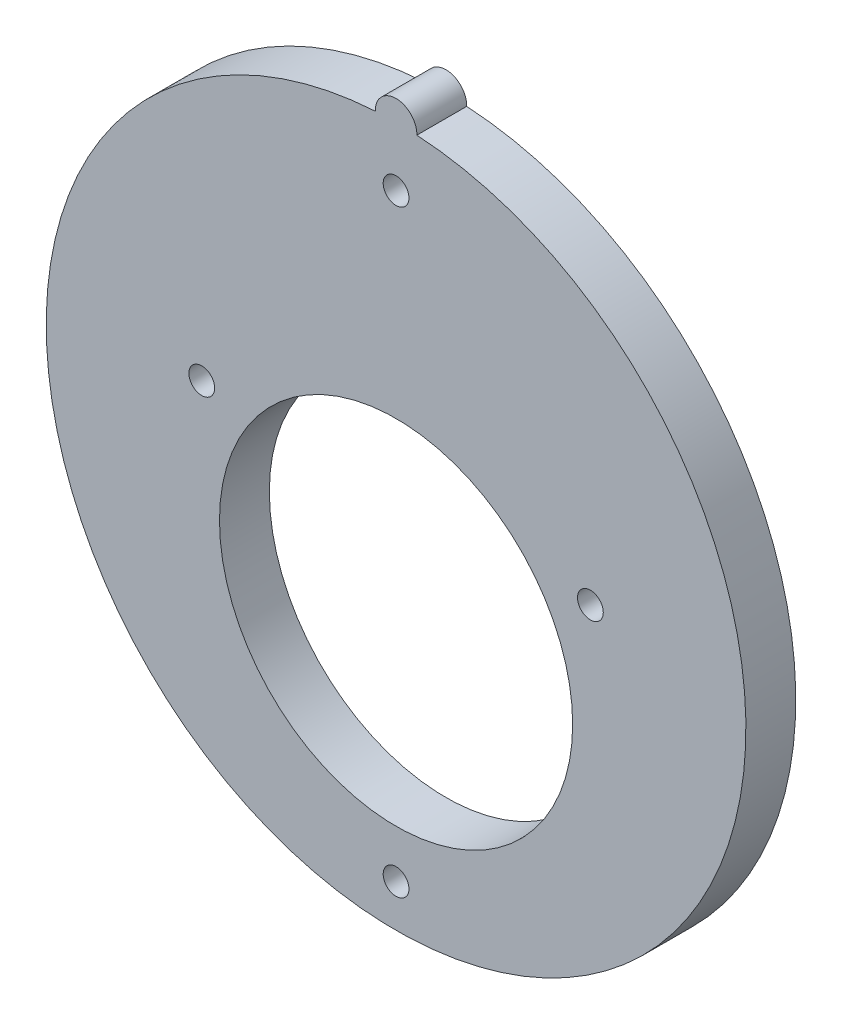
SolidWorks part; units mm, degrees
ref_plane "Płaszczyzna przednia" through (0, 0, 0) normal (0, 0, 1) x (1, 0, 0)
ref_plane "Płaszczyzna górna" through (0, 0, 0) normal (0, 1, 0) x (1, 0, 0)
ref_plane "Płaszczyzna prawa" through (0, 0, 0) normal (1, 0, 0) x (0, 0, -1)
sketch "Szkic1" plane through (0, 0, 0) normal (0, 0, 1) x (1, 0, 0)
  arc A0 (38.7806, 73.9078) -> (43.7784, 73.9078) centre (41.2795, 31.882) ccw
  arc A1 (43.7784, 73.9078) -> (38.7806, 73.9078) centre (41.2795, 73.982) ccw
  dimension "D1" = 84.2
  dimension "D2" = 5
extrude "Dodanie-wyciągnięcie1" add sketch "Szkic1" along normal blind 6
sketch "Szkic3" plane through (0, 0, 6) normal (0, 0, 1) x (1, 0, 0)
  line L0 (41.2795, 76.482) -> (41.2795, 1.7316) construction
  arc A1 (43.7784, 73.9078) -> (38.7806, 73.9078) centre (41.2795, 73.982) ccw construction
  circle A2 centre (41.2795, 21.882) radius 21.25
  arc A3 (38.7806, 73.9078) -> (43.7784, 73.9078) centre (41.2795, 31.882) ccw construction
  dimension "D1" = 42.5
  dimension "D2" = 10
extrude "Wytnij-wyciągnięcie1" cut sketch "Szkic3" against normal blind 10
sketch "Szkic4" plane through (0, 0, 6) normal (0, 0, 1) x (1, 0, 0)
  line L0 (41.2795, -10.218) -> (41.2795, -3.568) construction
  line L1 (41.2795, -3.568) -> (41.2795, 21.882) construction
  line L2 (17.8968, 35.382) -> (41.2795, 21.882) construction
  line L3 (41.2795, 21.882) -> (64.6622, 35.382) construction
  line L4 (41.2795, 21.882) -> (41.2795, 69.1257) construction
  arc A0 (38.7806, 73.9078) -> (43.7784, 73.9078) centre (41.2795, 31.882) ccw construction
  circle A1 centre (41.2795, -5.118) radius 1.55
  circle A2 centre (17.8968, 35.382) radius 1.55
  circle A3 centre (64.6622, 35.382) radius 1.55
  circle A4 centre (41.2795, 21.882) radius 21.25 construction
  circle A5 centre (41.2795, 66.882) radius 1.55
  dimension "D1" = 3.1
  dimension "D2" = 3.1
  dimension "D3" = 3.1
  dimension "D4" = 27
  dimension "D5" = 27
  dimension "D7" = 27
  dimension "D9" = 3.1
  dimension "D10" = 45
  dimension "D6" = 120
  dimension "D8" = 120
extrude "Wytnij-wyciągnięcie2" cut sketch "Szkic4" against normal blind 10
sketch "Szkic5" plane through (0, 0, 6) normal (0, 0, 1) x (1, 0, 0)
  line L0 (41.2795, 76.482) -> (41.2795, -7.4662) construction
  arc A0 (43.7784, 73.9078) -> (38.7806, 73.9078) centre (41.2795, 73.982) ccw construction
  point P6 (41.2795, 21.882)
equation "\"tolerancja_wpusy\"=0.2"
equation "\"dlugosc_wpustu_duzy\"=20"
equation "\"srednica_otworu_M3\"=3.1"
equation "\"szerokosc_nogi_T\"=3.1"
equation "\"dlugosc_T_30\"=11"
equation "\"grubosc_na_nakretke_kwadrat\"=2"
equation "\"szerokosc_na_nakretke_kwadrat\"=5.85"
equation "\"wyokosc_nadstawki_T\"=0.5"
equation "\"dlugosc_T_20_6\"=14"
equation "\"D1@Szkic4\"=\"srednica_otworu_M3\""
equation "\"D2@Szkic4\"=\"srednica_otworu_M3\""
equation "\"D3@Szkic4\"=\"srednica_otworu_M3\""
equation "\"D9@Szkic4\"=\"srednica_otworu_M3\""
